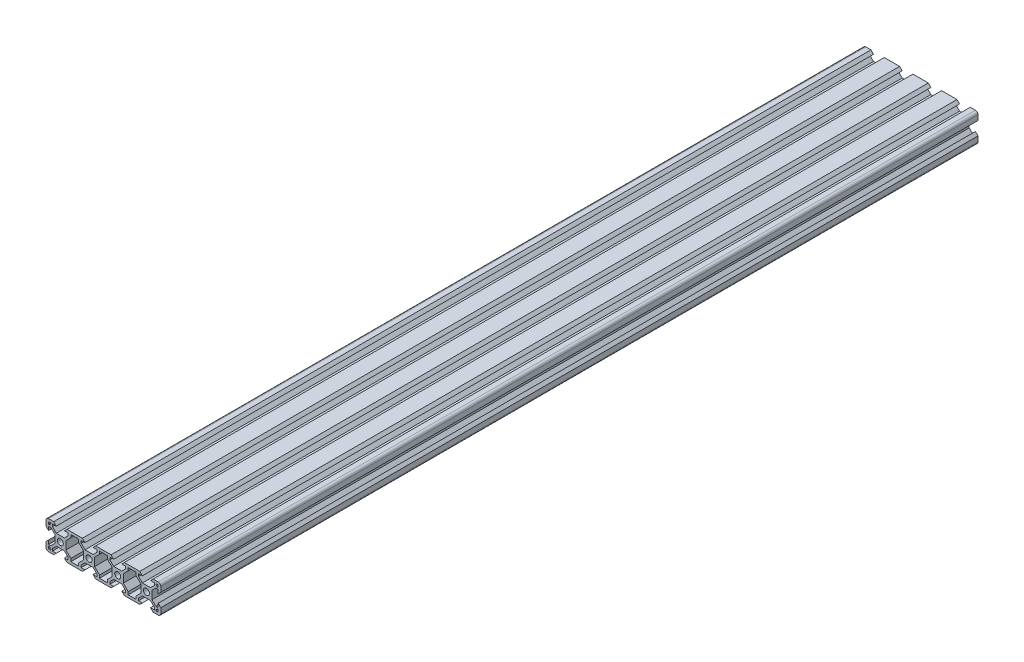
SolidWorks part; units mm, degrees
material "6063-T5"
ref_plane "Plane1" through (0, 0, 0) normal (0, 0, 1) x (1, 0, 0)
ref_plane "Plane2" through (0, 0, 0) normal (0, 1, 0) x (1, 0, 0)
ref_plane "Plane3" through (0, 0, 0) normal (1, 0, 0) x (0, 0, -1)
sketch "Sketch1" plane through (0, 0, 0) normal (0, 0, 1) x (1, 0, 0)
  line L0 (0, 0) -> (0, 10) construction
  line L1 (0, 0) -> (-40, 0) construction
  line L2 (-40, 10) -> (-30, 0) construction
  line L3 (-30, 0) -> (-20, 10) construction
  line L4 (-20, 10) -> (-10, 0) construction
  line L5 (-10, 0) -> (0, 10) construction
  line L6 (-10, 0) -> (-10, 10) construction
  line L7 (-20, 10) -> (-20, 0) construction
  line L8 (-40, 0) -> (-40, 10) construction
  line L9 (-38.2, 10) -> (-34.64, 10)
  line L10 (-34.64, 10) -> (-32.84, 8.2)
  line L11 (-32.84, 8.2) -> (-35.4993, 8.2)
  line L12 (-35.4993, 8.2) -> (-35.4993, 6.56)
  line L13 (-35.4993, 6.56) -> (-32.84, 3.9007)
  line L14 (-32.84, 3.9007) -> (-27.16, 3.9007)
  line L15 (-30, 0) -> (-30, 10) construction
  line L16 (-33.9007, 2.84) -> (-33.9007, 0)
  line L17 (-36.56, 5.4993) -> (-33.9007, 2.84)
  line L18 (-38.2, 5.4993) -> (-36.56, 5.4993)
  line L19 (-38.2, 2.84) -> (-38.2, 5.4993)
  line L20 (-40, 4.64) -> (-38.2, 2.84)
  line L21 (-40, 8.2) -> (-40, 4.64)
  line L22 (-38.2, 8.2) -> (-38.2, 6.5693)
  line L23 (-38.2, 6.5693) -> (-37.63, 6.5693)
  line L24 (-37.63, 6.5693) -> (-36.5693, 7.63)
  line L25 (-36.5693, 7.63) -> (-36.5693, 8.2)
  line L26 (-36.5693, 8.2) -> (-38.2, 8.2)
  line L27 (-17.3, 6.2393) -> (-17.3, 8.2)
  line L28 (-13.9007, 2.84) -> (-17.3, 6.2393)
  line L29 (-13.9007, -2.84) -> (-13.9007, 2.84)
  line L30 (-14.64, 10) -> (-12.84, 8.2)
  line L31 (-12.84, 8.2) -> (-15.4993, 8.2)
  line L32 (-15.4993, 8.2) -> (-15.4993, 6.56)
  line L33 (-15.4993, 6.56) -> (-12.84, 3.9007)
  line L34 (-12.84, 3.9007) -> (-7.16, 3.9007)
  line L35 (-5.36, 10) -> (-7.16, 8.2)
  line L36 (-7.16, 8.2) -> (-4.5007, 8.2)
  line L37 (-4.5007, 8.2) -> (-4.5007, 6.56)
  line L38 (-4.5007, 6.56) -> (-7.16, 3.9007)
  line L39 (-5.36, 10) -> (5.36, 10)
  line L40 (-6.0993, -2.84) -> (-6.0993, 2.84)
  line L41 (-6.0993, 2.84) -> (-2.7, 6.2393)
  line L42 (-2.7, 6.2393) -> (-2.7, 8.2)
  line L43 (-2.7, 8.2) -> (2.7, 8.2)
  line L44 (-25.36, 10) -> (-27.16, 8.2)
  line L45 (-7.16, 3.9007) -> (-6.0993, 2.84) construction
  line L46 (-36.5693, -7.63) -> (-36.5693, -8.2)
  line L47 (-37.63, -6.5693) -> (-36.5693, -7.63)
  line L48 (-38.2, -6.5693) -> (-37.63, -6.5693)
  line L49 (-38.2, -8.2) -> (-38.2, -6.5693)
  line L50 (-27.16, 8.2) -> (-24.5007, 8.2)
  line L51 (-24.5007, 8.2) -> (-24.5007, 6.56)
  line L52 (-24.5007, 6.56) -> (-27.16, 3.9007)
  line L53 (-25.36, 10) -> (-14.64, 10)
  line L54 (-26.0993, -2.84) -> (-26.0993, 2.84)
  line L55 (-26.0993, 2.84) -> (-22.7, 6.2393)
  line L56 (-22.7, 6.2393) -> (-22.7, 8.2)
  line L57 (-22.7, 8.2) -> (-17.3, 8.2)
  line L58 (-27.16, 3.9007) -> (-26.0993, 2.84) construction
  line L59 (-26.0993, 2.84) -> (-26.0962, 2.8177) construction
  line L60 (-36.5693, -8.2) -> (-38.2, -8.2)
  line L61 (-26.0993, -2.84) -> (-22.7, -6.2393)
  line L62 (-22.7, -6.2393) -> (-22.7, -8.2)
  line L63 (-22.7, -8.2) -> (-17.3, -8.2)
  line L64 (-17.3, -6.2393) -> (-17.3, -8.2)
  line L65 (-13.9007, -2.84) -> (-17.3, -6.2393)
  line L66 (-2.7, -8.2) -> (2.7, -8.2)
  line L67 (-2.7, -6.2393) -> (-2.7, -8.2)
  line L68 (-6.0993, -2.84) -> (-2.7, -6.2393)
  line L69 (-5.36, -10) -> (5.36, -10)
  line L70 (-5.36, -10) -> (-7.16, -8.2)
  line L71 (-7.16, -8.2) -> (-4.5007, -8.2)
  line L72 (-4.5007, -8.2) -> (-4.5007, -6.56)
  line L73 (-4.5007, -6.56) -> (-7.16, -3.9007)
  line L74 (-12.84, -3.9007) -> (-7.16, -3.9007)
  line L75 (-15.4993, -6.56) -> (-12.84, -3.9007)
  line L76 (-15.4993, -8.2) -> (-15.4993, -6.56)
  line L77 (-12.84, -8.2) -> (-15.4993, -8.2)
  line L78 (-14.64, -10) -> (-12.84, -8.2)
  line L79 (-25.36, -10) -> (-14.64, -10)
  line L80 (-25.36, -10) -> (-27.16, -8.2)
  line L81 (-27.16, -8.2) -> (-24.5007, -8.2)
  line L82 (-24.5007, -8.2) -> (-24.5007, -6.56)
  line L83 (-24.5007, -6.56) -> (-27.16, -3.9007)
  line L84 (-32.84, -3.9007) -> (-27.16, -3.9007)
  line L85 (-35.4993, -6.56) -> (-32.84, -3.9007)
  line L86 (-35.4993, -8.2) -> (-35.4993, -6.56)
  line L87 (-32.84, -8.2) -> (-35.4993, -8.2)
  line L88 (-34.64, -10) -> (-32.84, -8.2)
  line L89 (-38.2, -10) -> (-34.64, -10)
  line L90 (-40, -8.2) -> (-40, -4.64)
  line L91 (-40, -4.64) -> (-38.2, -2.84)
  line L92 (-38.2, -2.84) -> (-38.2, -5.4993)
  line L93 (-38.2, -5.4993) -> (-36.56, -5.4993)
  line L94 (-36.56, -5.4993) -> (-33.9007, -2.84)
  line L95 (-33.9007, -2.84) -> (-33.9007, 0)
  line L96 (36.5693, 8.2) -> (38.2, 8.2)
  line L97 (36.5693, 7.63) -> (36.5693, 8.2)
  line L98 (37.63, 6.5693) -> (36.5693, 7.63)
  line L99 (38.2, 6.5693) -> (37.63, 6.5693)
  line L100 (38.2, 8.2) -> (38.2, 6.5693)
  line L101 (36.5693, -8.2) -> (38.2, -8.2)
  line L102 (36.5693, -7.63) -> (36.5693, -8.2)
  line L103 (37.63, -6.5693) -> (36.5693, -7.63)
  line L104 (38.2, -6.5693) -> (37.63, -6.5693)
  line L105 (38.2, -8.2) -> (38.2, -6.5693)
  line L106 (13.9007, -2.84) -> (17.3, -6.2393)
  line L107 (17.3, -6.2393) -> (17.3, -8.2)
  line L108 (22.7, -8.2) -> (17.3, -8.2)
  line L109 (22.7, -6.2393) -> (22.7, -8.2)
  line L110 (26.0993, -2.84) -> (22.7, -6.2393)
  line L111 (26.0993, -2.84) -> (26.0993, 2.84)
  line L112 (26.0993, 2.84) -> (22.7, 6.2393)
  line L113 (22.7, 6.2393) -> (22.7, 8.2)
  line L114 (22.7, 8.2) -> (17.3, 8.2)
  line L115 (17.3, 6.2393) -> (17.3, 8.2)
  line L116 (13.9007, 2.84) -> (17.3, 6.2393)
  line L117 (13.9007, -2.84) -> (13.9007, 2.84)
  line L118 (2.7, -6.2393) -> (2.7, -8.2)
  line L119 (6.0993, -2.84) -> (2.7, -6.2393)
  line L120 (6.0993, -2.84) -> (6.0993, 2.84)
  line L121 (6.0993, 2.84) -> (2.7, 6.2393)
  line L122 (2.7, 6.2393) -> (2.7, 8.2)
  line L123 (5.36, -10) -> (7.16, -8.2)
  line L124 (7.16, -8.2) -> (4.5007, -8.2)
  line L125 (4.5007, -8.2) -> (4.5007, -6.56)
  line L126 (4.5007, -6.56) -> (7.16, -3.9007)
  line L127 (12.84, -3.9007) -> (7.16, -3.9007)
  line L128 (15.4993, -6.56) -> (12.84, -3.9007)
  line L129 (15.4993, -8.2) -> (15.4993, -6.56)
  line L130 (12.84, -8.2) -> (15.4993, -8.2)
  line L131 (14.64, -10) -> (12.84, -8.2)
  line L132 (25.36, -10) -> (14.64, -10)
  line L133 (25.36, -10) -> (27.16, -8.2)
  line L134 (27.16, -8.2) -> (24.5007, -8.2)
  line L135 (24.5007, -8.2) -> (24.5007, -6.56)
  line L136 (24.5007, -6.56) -> (27.16, -3.9007)
  line L137 (32.84, -3.9007) -> (27.16, -3.9007)
  line L138 (35.4993, -6.56) -> (32.84, -3.9007)
  line L139 (35.4993, -8.2) -> (35.4993, -6.56)
  line L140 (32.84, -8.2) -> (35.4993, -8.2)
  line L141 (34.64, -10) -> (32.84, -8.2)
  line L142 (38.2, -10) -> (34.64, -10)
  line L143 (40, -8.2) -> (40, -4.64)
  line L144 (40, -4.64) -> (38.2, -2.84)
  line L145 (38.2, -2.84) -> (38.2, -5.4993)
  line L146 (38.2, -5.4993) -> (36.56, -5.4993)
  line L147 (36.56, -5.4993) -> (33.9007, -2.84)
  line L148 (33.9007, -2.84) -> (33.9007, 0)
  line L149 (33.9007, 2.84) -> (33.9007, 0)
  line L150 (36.56, 5.4993) -> (33.9007, 2.84)
  line L151 (38.2, 5.4993) -> (36.56, 5.4993)
  line L152 (38.2, 2.84) -> (38.2, 5.4993)
  line L153 (40, 4.64) -> (38.2, 2.84)
  line L154 (40, 8.2) -> (40, 4.64)
  line L155 (38.2, 10) -> (34.64, 10)
  line L156 (34.64, 10) -> (32.84, 8.2)
  line L157 (32.84, 8.2) -> (35.4993, 8.2)
  line L158 (35.4993, 8.2) -> (35.4993, 6.56)
  line L159 (35.4993, 6.56) -> (32.84, 3.9007)
  line L160 (32.84, 3.9007) -> (27.16, 3.9007)
  line L161 (24.5007, 6.56) -> (27.16, 3.9007)
  line L162 (24.5007, 8.2) -> (24.5007, 6.56)
  line L163 (27.16, 8.2) -> (24.5007, 8.2)
  line L164 (25.36, 10) -> (27.16, 8.2)
  line L165 (25.36, 10) -> (14.64, 10)
  line L166 (14.64, 10) -> (12.84, 8.2)
  line L167 (12.84, 8.2) -> (15.4993, 8.2)
  line L168 (15.4993, 8.2) -> (15.4993, 6.56)
  line L169 (15.4993, 6.56) -> (12.84, 3.9007)
  line L170 (12.84, 3.9007) -> (7.16, 3.9007)
  line L171 (4.5007, 6.56) -> (7.16, 3.9007)
  line L172 (4.5007, 8.2) -> (4.5007, 6.56)
  line L173 (7.16, 8.2) -> (4.5007, 8.2)
  line L174 (5.36, 10) -> (7.16, 8.2)
  circle A0 centre (-30, 0) radius 2.1
  circle A1 centre (-10, 0) radius 2.1
  arc A2 (-38.2, 10) -> (-40, 8.2) centre (-38.2, 8.2) ccw
  arc A3 (-38.2, -10) -> (-40, -8.2) centre (-38.2, -8.2) cw
  circle A4 centre (30, 0) radius 2.1
  circle A5 centre (10, 0) radius 2.1
  arc A6 (38.2, -10) -> (40, -8.2) centre (38.2, -8.2) ccw
  arc A7 (38.2, 10) -> (40, 8.2) centre (38.2, 8.2) cw
  point P21 (-37.0997, 7.0997)
  point P36 (-20, 8.2)
  point P47 (-10, 3.9007)
  point P54 (-6.6297, 3.3703)
  point P61 (-30, 3.9007)
  point P71 (-26.0993, 0)
  point P76 (-13.9007, 0)
  point P80 (-6.0993, 0)
  point P135 (0, -8.2)
  point P140 (0, 8.2)
  point P141 (0, -10)
  dimension "D3" = 4.2
  dimension "D4" = 4.2
  dimension "D1" = 40
  dimension "D2" = 10
  dimension "D5" = 5.68
  dimension "D6" = 1.5
  dimension "D7" = 1.64
  dimension "D8" = 1.8
  dimension "D9" = 1.07
  dimension "D11" = 5.4
extrude "Extrude1" add sketch "Sketch1" along normal mid plane 569.6
